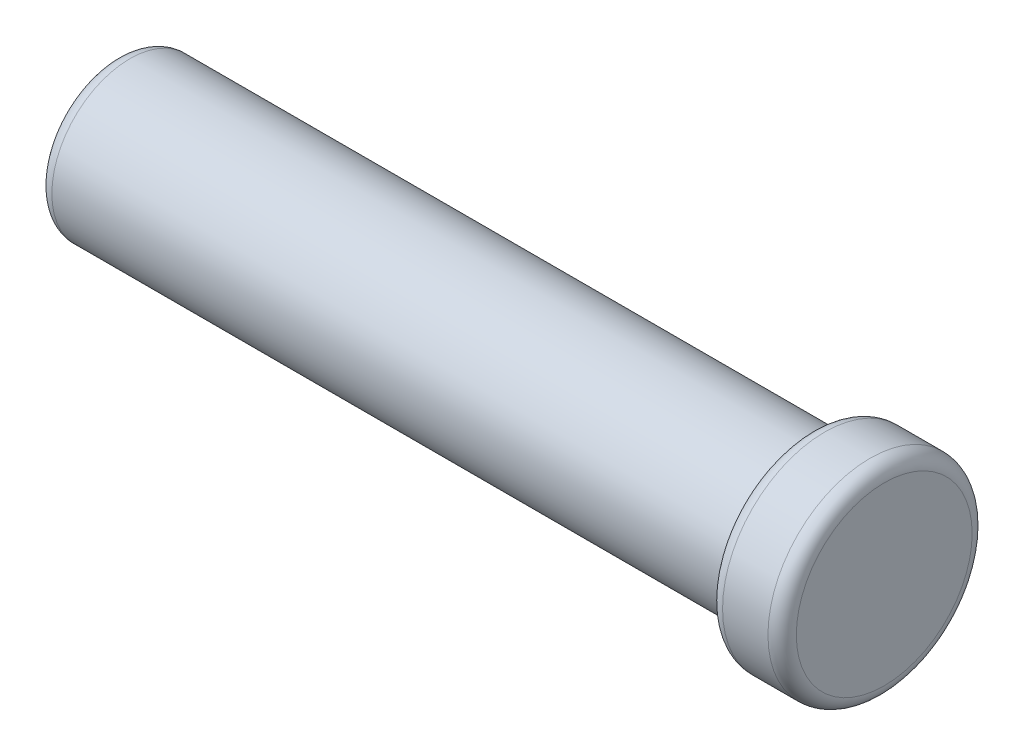
SolidWorks part; units mm, degrees
ref_plane "Front Plane" through (0, 0, 0) normal (0, 0, 1) x (1, 0, 0)
ref_plane "Top Plane" through (0, 0, 0) normal (0, 1, 0) x (1, 0, 0)
ref_plane "Right Plane" through (0, 0, 0) normal (1, 0, 0) x (0, 0, -1)
sketch "Sketch1" plane through (0, 0, 0) normal (0, 1, 0) x (1, 0, 0)
  line L0 (0, 0) -> (27.1, 0)
  line L1 (27.1, 0) -> (27.1, 3.6)
  line L2 (27.1, 3.6) -> (24.5, 3.6)
  line L3 (24.5, 3.6) -> (24.5, 2.75)
  line L4 (24.5, 2.75) -> (0, 2.75)
  line L6 (0, 2.75) -> (0, 0)
revolve "Revolve1" add sketch "Sketch1" angle 360 about L0
fillet "Fillet1" radius 0.5 1 edges at (27.1, 0, 3.6)
fillet "Fillet2" radius 0.5 1 edges at (0, 0, 2.75)
fillet "Fillet3" radius 0.5 1 edges at (24.5, 0, 3.6)
